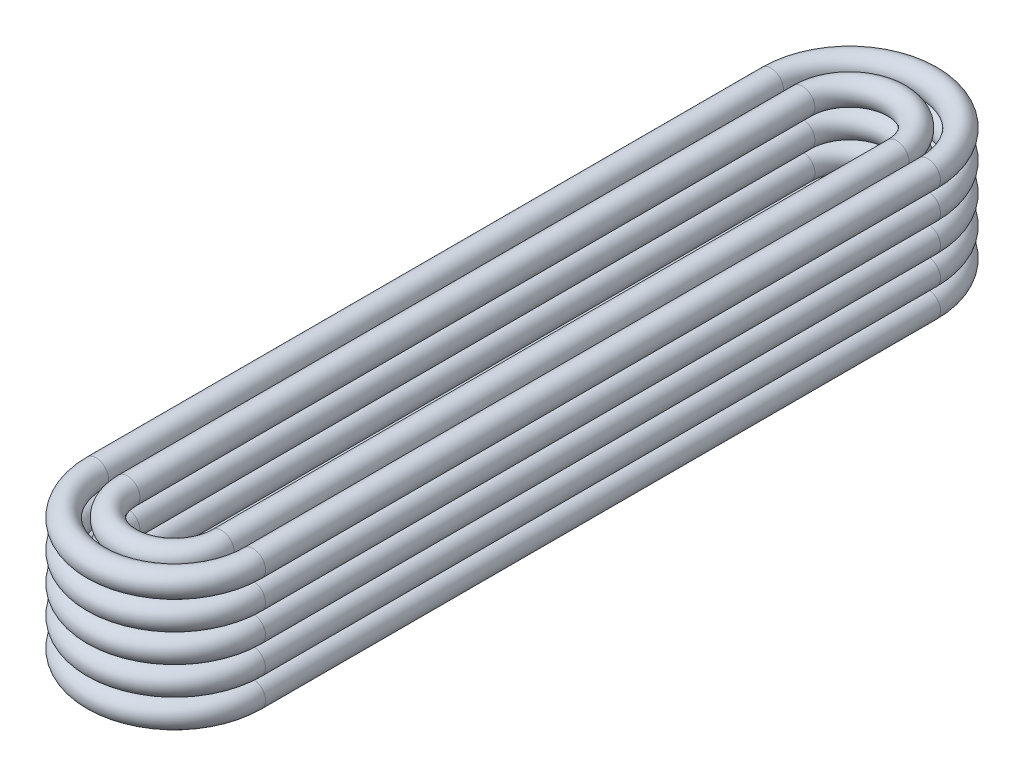
SolidWorks part; units mm, degrees
material "Cuivre"
ref_plane "Plan de face" through (0, 0, 0) normal (0, 0, 1) x (1, 0, 0)
ref_plane "Plan de dessus" through (0, 0, 0) normal (0, 1, 0) x (1, 0, 0)
ref_plane "Plan de droite" through (0, 0, 0) normal (1, 0, 0) x (0, 0, -1)
sketch "Esquisse1" plane through (0, 0, 0) normal (0, 1, 0) x (1, 0, 0)
  line L0 (-3, -21.5) -> (-3, 21.5)
  line L1 (3, -21.5) -> (3, 21.5)
  line L2 (0, 21.5) -> (0, -21.5) construction
  arc A0 (3, 21.5) -> (-3, 21.5) centre (0, 21.5) ccw
  arc A1 (-3, -21.5) -> (3, -21.5) centre (0, -21.5) ccw
  dimension "D1" = 43
  dimension "D2" = 6
sketch "Esquisse2" plane through (0, 0, 0) normal (0, 0, 1) x (1, 0, 0)
  circle A0 centre (-3, 0) radius 0.8
  dimension "D1" = 1.6
sweep "Balayage1" add profiles "Esquisse2" path "Esquisse1"
sketch "Esquisse3" plane through (0, 0, 0) normal (0, 1, 0) x (1, 0, 0)
  line L4 (-5, 21.5) -> (-5, -21.5)
  line L5 (5, -21.5) -> (5, 21.5)
  line L6 (-5, 21.5) -> (-5, -21.5)
  line L7 (5, -21.5) -> (5, 21.5)
  arc A4 (5, 21.5) -> (-5, 21.5) centre (0, 21.5) ccw
  arc A5 (-5, -21.5) -> (5, -21.5) centre (0, -21.5) ccw
  arc A6 (5, 21.5) -> (-5, 21.5) centre (0, 21.5) ccw
  arc A7 (-5, -21.5) -> (5, -21.5) centre (0, -21.5) ccw
  dimension "D1" = 2
sketch "Esquisse4" plane through (0, 0, 0) normal (0, 0, 1) x (1, 0, 0)
  circle A0 centre (-5, 0) radius 0.8
  circle A1 centre (-3, 0) radius 0.8 construction
sweep "Balayage2" add profiles "Esquisse4" path "Esquisse3"
sketch "Esquisse5" plane through (0, 0, 0) normal (0, 0, 1) x (1, 0, 0)
  line L0 (0, 0) -> (0, 6)
  line L1 (3, 0) -> (-3, 0) construction
pattern_linear "Répétition linéaire1" count 5 spacing 1.8 along (0, 1, 0) of bodies 101 102
